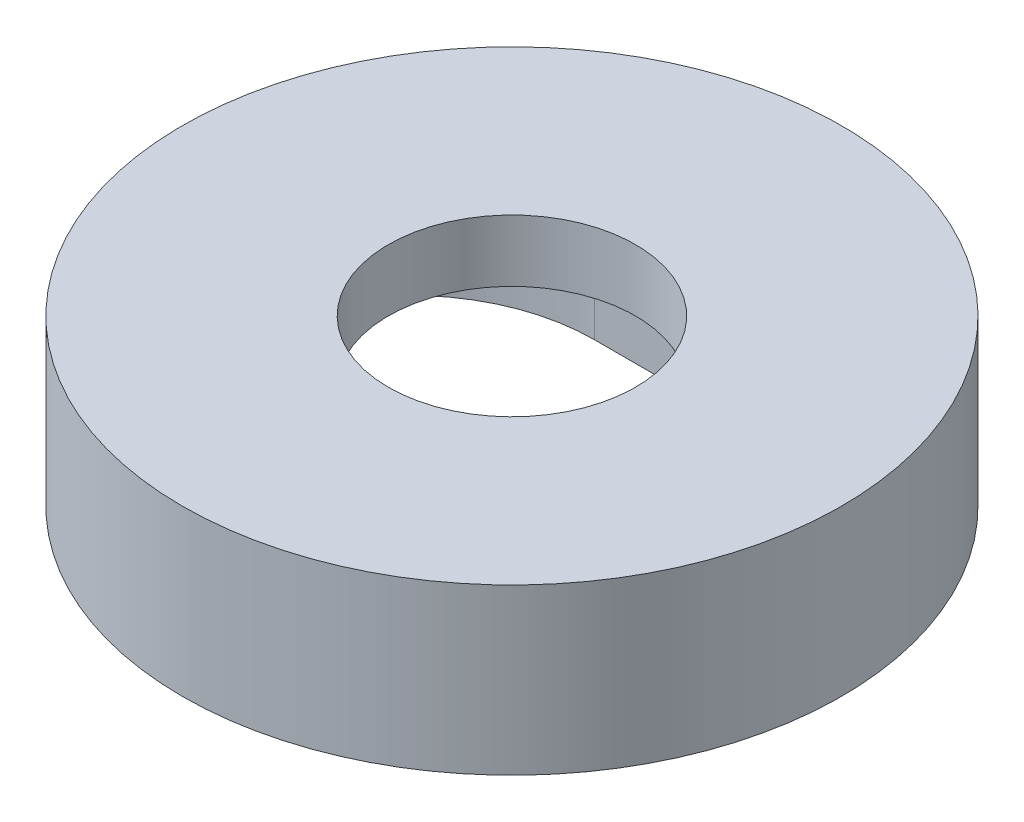
SolidWorks part; units mm, degrees
material "Laiton"
ref_plane "Plan de face" through (0, 0, 0) normal (0, 0, 1) x (1, 0, 0)
ref_plane "Plan de dessus" through (0, 0, 0) normal (0, 1, 0) x (1, 0, 0)
ref_plane "Plan de droite" through (0, 0, 0) normal (1, 0, 0) x (0, 0, -1)
sketch "Esquisse2" plane through (0, 0, 0) normal (0, 1, 0) x (1, 0, 0)
  circle A0 centre (0, 0) radius 16
  dimension "D1" = 32
extrude "Boss.-Extru.1" add sketch "Esquisse2" along normal blind 8
sketch "Esquisse1" plane through (0, 0, 0) normal (0, 1, 0) x (1, 0, 0)
  line L0 (0, 0) -> (0, 11.7653) construction
  line L1 (-12.5607, 0) -> (0, 0) construction
  line L2 (-5, 0) -> (5, 0) construction
  line L3 (-5, 9) -> (5, 9)
  line L4 (-5, -9) -> (5, -9)
  arc A0 (-5, 9) -> (-5, -9) centre (-5, 0) ccw
  arc A1 (5, -9) -> (5, 9) centre (5, 0) ccw
  ellipse E0 centre (0, 0) end of major axis (-14, 0) minor radius 9 construction
  point P11 (0, 0)
  dimension "D1" = 9
  dimension "D2" = 14
extrude "Enlèv. mat.-Extru.1" cut sketch "Esquisse1" along normal blind 5
sketch "Esquisse3" plane through (0, 8, 0) normal (0, 1, 0) x (1, 0, 0)
  circle A0 centre (0, 0) radius 6
  dimension "D1" = 12
extrude "Enlèv. mat.-Extru.2" cut sketch "Esquisse3" against normal through all
